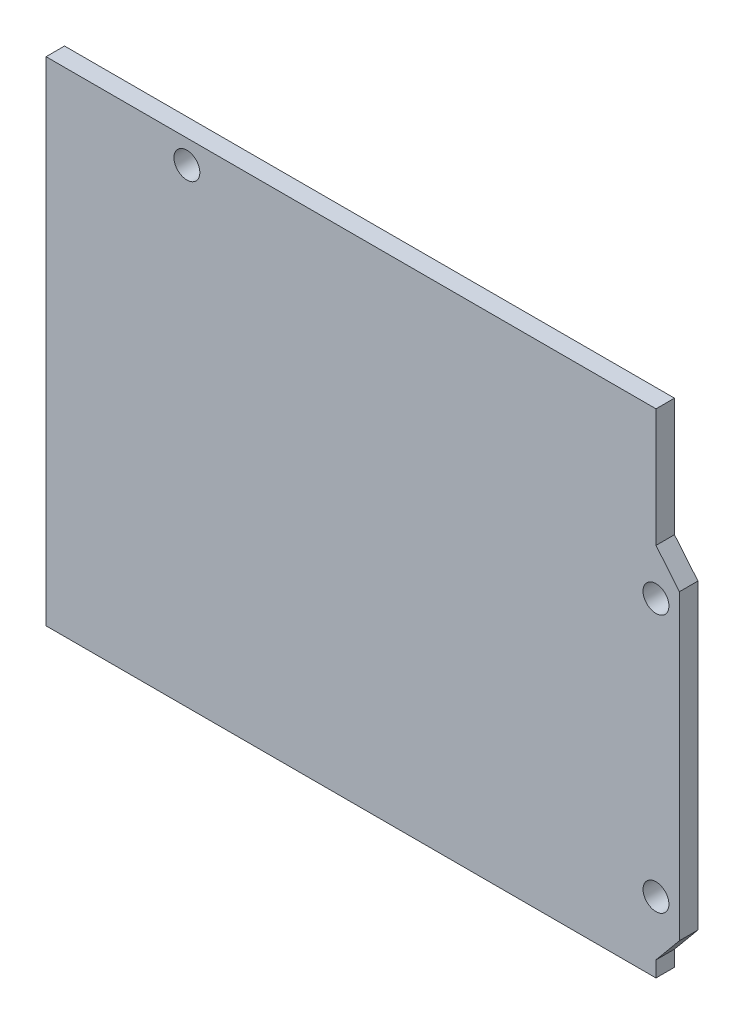
SolidWorks part; units mm, degrees
ref_plane "Front Plane" through (0, 0, 0) normal (0, 0, 1) x (1, 0, 0)
ref_plane "Top Plane" through (0, 0, 0) normal (0, 1, 0) x (1, 0, 0)
ref_plane "Right Plane" through (0, 0, 0) normal (1, 0, 0) x (0, 0, -1)
sketch "Sketch2" plane through (0, 0, 0) normal (0, 0, 1) x (1, 0, 0)
  line L0 (0, 0) -> (0, 53.34)
  line L1 (0, 53.34) -> (66, 53.34)
  line L3 (66, 0) -> (66, 1.6991)
  line L4 (66, 1.6991) -> (68.54, 4.7655)
  line L8 (0, 0) -> (66, 0)
  line L10 (68.54, 4.7655) -> (68.54, 37.4736)
  line L12 (66, 40.54) -> (68.54, 37.4736)
  line L13 (66, 53.34) -> (66, 40.54)
  circle A3 centre (15.24, 50.8) radius 1.4
  circle A4 centre (66, 35.56) radius 1.4
  circle A5 centre (66, 7.62) radius 1.4
  dimension "D1" = 7.62
  dimension "D2" = 35.56
  dimension "D3" = 2.8
  dimension "D6" = 2.8
  dimension "D10" = 2.54
  dimension "D4" = 66
  dimension "D5" = 53.34
  dimension "D7" = 2.54
  dimension "D8" = 15.24
  dimension "D9" = 12.8
  dimension "D11" = 2.54
  dimension "D12" = 68.54
extrude "Boss-Extrude1" add sketch "Sketch2" against normal blind 2
